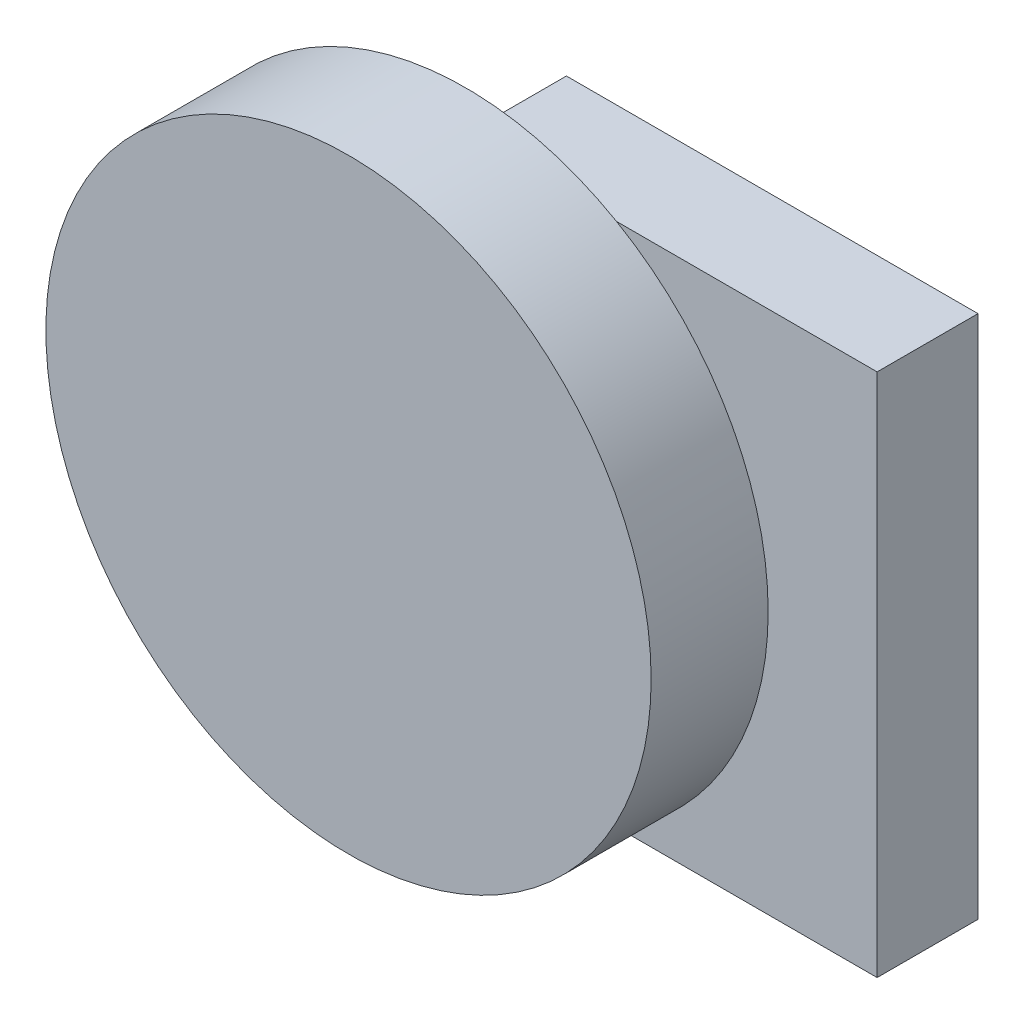
SolidWorks part; units mm, degrees
ref_plane "前视基准面" through (0, 0, 0) normal (0, 0, 1) x (1, 0, 0)
ref_plane "上视基准面" through (0, 0, 0) normal (0, 1, 0) x (1, 0, 0)
ref_plane "右视基准面" through (0, 0, 0) normal (1, 0, 0) x (0, 0, -1)
sketch "草图1" plane through (0, 0, 0) normal (0, 0, 1) x (1, 0, 0)
  line L1 (0, 0) -> (-10.2, 0)
  line L2 (0, 0) -> (0, 13)
  line L3 (0, 13) -> (-10.2, 13)
  line L4 (-10.2, 0) -> (-10.2, 13)
  dimension "D1" = 13
  dimension "D2" = 10.2
extrude "凸台-拉伸1" add sketch "草图1" along normal blind 2.5
sketch "草图2" plane through (0, 0, 2.5) normal (0, 0, 1) x (1, 0, 0)
  line L0 (-10.2, 13) -> (-10.2, 0) construction
  circle A0 centre (-10.2, 6.5) radius 7.5
  point P0 (-10.2, 6.5)
  dimension "D1" = 15
extrude "凸台-拉伸2" add sketch "草图2" along normal blind 2.9
